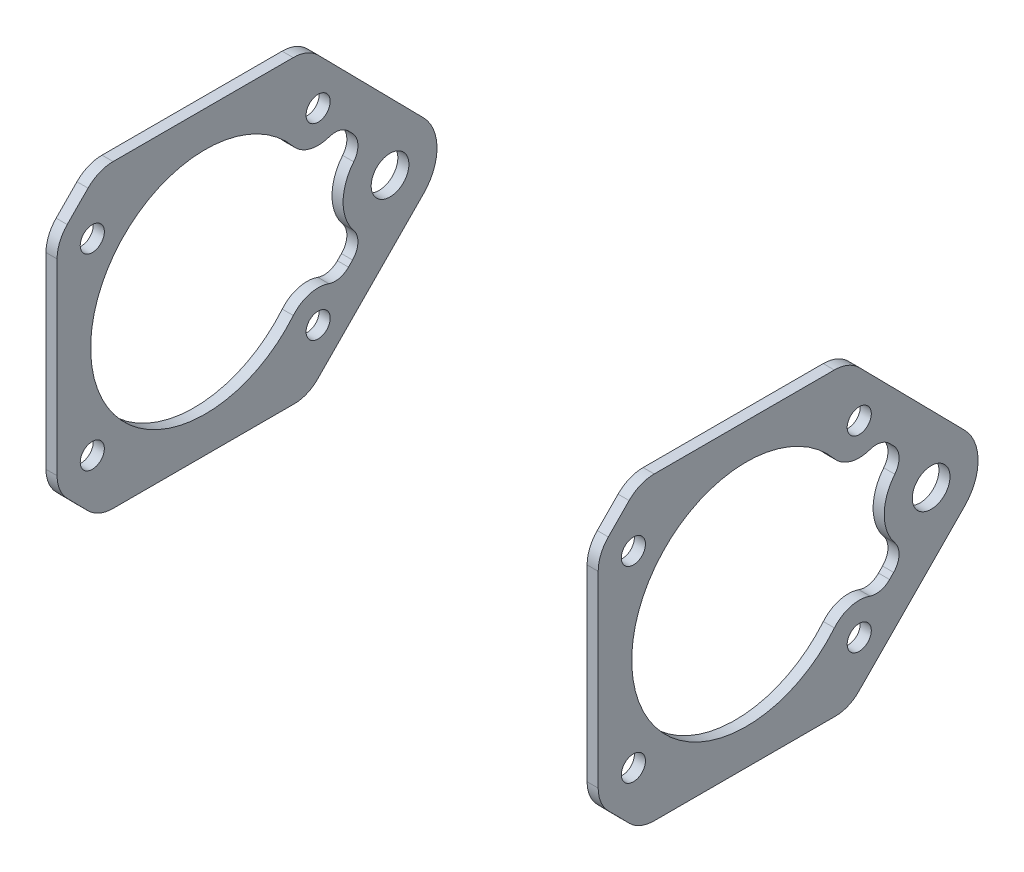
SolidWorks part; units mm, degrees
ref_plane "Front Plane" through (0, 0, 0) normal (0, 0, 1) x (1, 0, 0)
ref_plane "Top Plane" through (0, 0, 0) normal (0, 1, 0) x (1, 0, 0)
ref_plane "Right Plane" through (0, 0, 0) normal (1, 0, 0) x (0, 0, -1)
sketch "Sketch1" plane through (37.35, 0, 0) normal (-1, 0, 0) x (0, 0, 1)
  line L0 (-4.5233, 4.4567) -> (9.7073, 18.9)
  line L1 (13.0998, 20.32) -> (37.4636, 20.32)
  line L2 (45.0415, 12.7) -> (45.0415, -12.7)
  line L4 (37.4636, -20.32) -> (12.9337, -20.32)
  line L5 (9.8239, -19.0184) -> (-4.5233, -4.4567)
  line L7 (5.6234, -7.9694) -> (5.0726, -7.4104)
  line L8 (5.0726, 7.4104) -> (5.6234, 7.9694)
  line L9 (43.6715, 16.0425) -> (40.8561, 18.9)
  line L10 (11.43, 20.32) -> (147.2651, 20.32) construction
  line L11 (25.2817, 20.32) -> (25.2817, 7.2204) construction
  line L12 (0, 0) -> (51.1358, 0) construction
  line L13 (43.6715, -16.0425) -> (40.8561, -18.9)
  line L14 (157.5652, -20.32) -> (0, -20.32) construction
  arc A0 (37.4636, 20.32) -> (40.8561, 18.9) centre (37.4636, 15.5575) cw
  arc A1 (13.0842, -9.9091) -> (13.0842, 9.9091) centre (25.0031, 0) ccw
  arc A2 (4.9157, 4.0198) -> (4.9157, -4.0198) centre (0, 0) cw
  arc A3 (-4.5233, 4.4567) -> (-4.5233, -4.4567) centre (0, 0) ccw
  arc A5 (8.2767, -8.5824) -> (13.0842, -9.9091) centre (9.7272, -12.7) cw
  arc A6 (13.0842, 9.9091) -> (8.2767, 8.5824) centre (9.7272, 12.7) cw
  arc A7 (8.2767, -8.5824) -> (5.6234, -7.9694) centre (7.4327, -6.1867) cw
  arc A8 (5.0726, -7.4104) -> (4.9157, -4.0198) centre (6.882, -5.6277) cw
  arc A9 (9.8239, -19.0184) -> (12.9337, -20.32) centre (12.9337, -15.9544) ccw
  arc A10 (43.6715, -16.0425) -> (45.0415, -12.7) centre (40.279, -12.7) ccw
  arc A11 (45.0415, 12.7) -> (43.6715, 16.0425) centre (40.279, 12.7) ccw
  arc A12 (13.0998, 20.32) -> (9.7073, 18.9) centre (13.0998, 15.5575) ccw
  arc A13 (37.5725, -16.6187) -> (42.6573, -8.5739) centre (40.279, -12.7) ccw construction
  arc A14 (42.6573, 8.5739) -> (37.5725, 16.6187) centre (40.279, 12.7) ccw construction
  arc A17 (4.9157, 4.0198) -> (5.0726, 7.4104) centre (6.882, 5.6277) cw
  arc A18 (5.6234, 7.9694) -> (8.2767, 8.5824) centre (7.4327, 6.1867) cw
  circle A19 centre (9.7272, 12.7) radius 1.632 construction
  circle A20 centre (9.7272, 12.7) radius 1.632
  circle A21 centre (40.279, 12.7) radius 1.632 construction
  circle A22 centre (40.279, -12.7) radius 1.632 construction
  circle A23 centre (9.7272, -12.7) radius 1.632 construction
  circle A24 centre (40.279, 12.7) radius 1.6319
  circle A25 centre (40.279, -12.7) radius 1.6319
  circle A26 centre (9.7272, -12.7) radius 1.632
  circle A27 centre (25.0031, 0) radius 15.5 construction
  arc A28 (37.4636, -20.32) -> (40.8561, -18.9) centre (37.4636, -15.5575) ccw
  dimension "D1" = 6.35
  dimension "D2" = 2.54
  dimension "D3" = 4.7625
  dimension "D4" = 4.7625
extrude "Boss-Extrude1" add sketch "Sketch1" along normal blind 1.5
sketch "Sketch4" [suppressed] plane through (35.85, 0, 0) normal (-1, 0, 0) x (0, 0, 1)
  line L0 (18.3837, 17.4625) -> (31.6225, 17.4625)
  line L1 (37.4636, 20.32) -> (13.0998, 20.32) construction
  line L2 (18.3837, -17.4625) -> (31.6225, -17.4625)
  line L3 (12.9337, -20.32) -> (37.4636, -20.32) construction
  arc A0 (18.3837, -17.4625) -> (31.6225, -17.4625) centre (25.0031, 0) ccw
  arc A1 (31.6225, 17.4625) -> (18.3837, 17.4625) centre (25.0031, 0) ccw
  arc A2 (13.0842, -9.9091) -> (13.0842, 9.9091) centre (25.0031, 0) ccw construction
  dimension "D1" = 3.175
extrude "Boss-Extrude2" [suppressed] add sketch "Sketch4" against normal up to surface (1.5 mm away)
fillet "Fillet1" [suppressed] radius 6.35
hole_wizard "#10 Clearance Hole1" positions "Sketch2" profile "Sketch3" hole size "#10" standard "ANSI Inch" end condition up to next
sketch "Sketch2" plane through (35.85, 0, 0) normal (-1, 0, 0) x (0, 0, 1)
  point P0 (0, 0)
sketch "Sketch3" plane through (35.85, 0, 0) normal (0, 1, 0) x (0, 0, 1)
  line L0 (0, 0) -> (0, 1.5)
  line L1 (0, 1.5) -> (2.5527, 1.5)
  line L2 (2.5527, 1.5) -> (2.5527, 0)
  line L5 (2.5527, 0) -> (0, 0)
  line L11 (0, -6.35) -> (0, 107.95) construction
  dimension "Thru Hole Dia." = 5.1054
  dimension "Thru Hole Depth" = 1.5
mirror "Mirror2" about plane through (0, 0, 0) normal (1, 0, 0) of bodies 102
equation "\"D1@Boss-Extrude1\"=1.5mm"
equation "\"D3@Sketch1\"=\"D4@Sketch1\""
